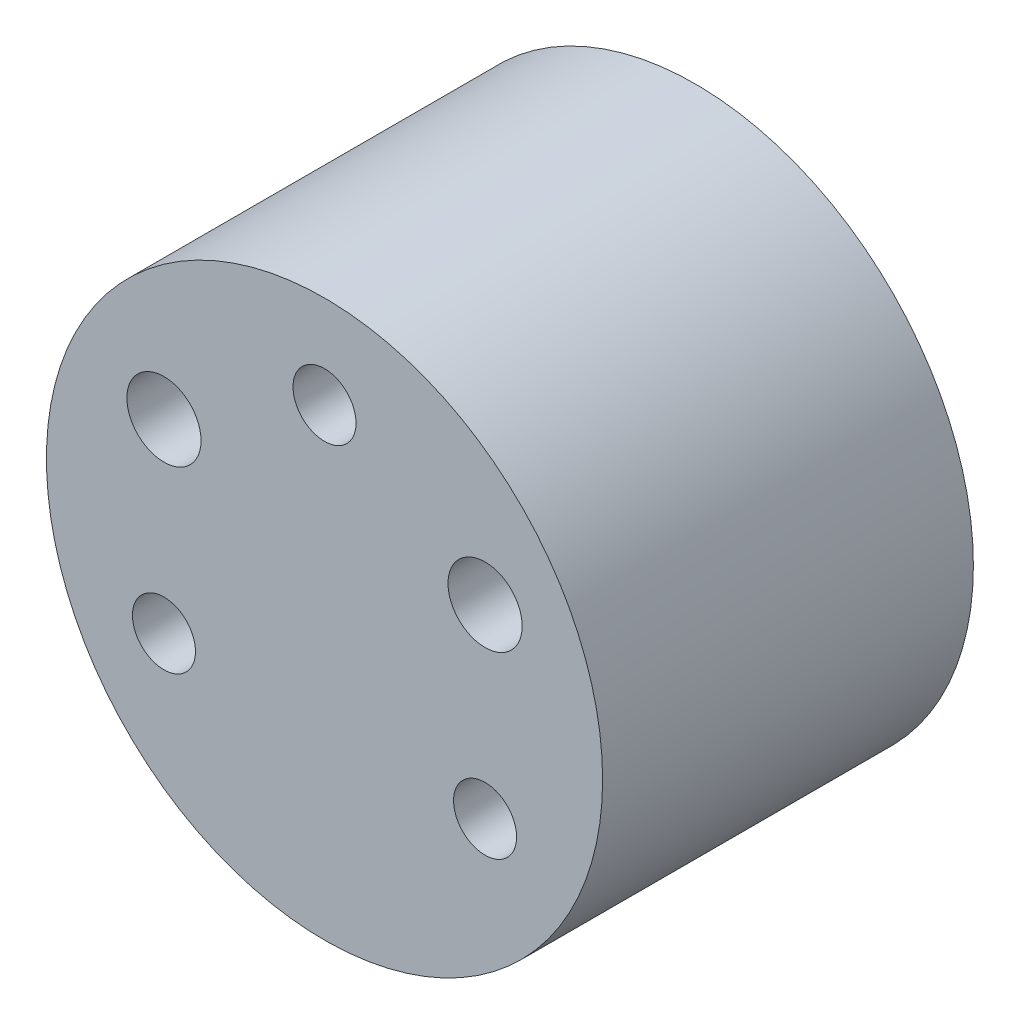
SolidWorks part; units mm, degrees
ref_plane "Plano frontal" through (0, 0, 0) normal (0, 0, 1) x (1, 0, 0)
ref_plane "Plano superior" through (0, 0, 0) normal (0, 1, 0) x (1, 0, 0)
ref_plane "Plano direito" through (0, 0, 0) normal (1, 0, 0) x (0, 0, -1)
sketch "Esboço1" plane through (0, 0, 0) normal (0, 0, 1) x (1, 0, 0)
  circle A0 centre (0, 235) radius 30 construction
  circle A1 centre (0, 235) radius 30
extrude "Ressalto-extrusão1" add sketch "Esboço1" along normal blind 40
hole_wizard "Furo roscado de M81" positions "Esboço2" profile "Esboço3" tap size "M8" standard "DIN"
sketch "Esboço2" plane through (0, 0, 40) normal (0, 0, 1) x (1, 0, 0)
  point P2 (-17.3205, 225)
  point P5 (0, 255)
  point P11 (17.3205, 225)
sketch "Esboço3" plane through (-17.3205, 225, 40) normal (1, 0, 0) x (0, -1, 0)
  line L0 (0, 0) -> (0, 32.0429)
  line L1 (0, 32.0429) -> (3.4, 30)
  line L2 (3.4, 30) -> (3.4, 0)
  line L5 (3.4, 0) -> (0, 0)
  line L10 (0, 32.0429) -> (-3.4, 30) construction
  line L11 (0, -6.35) -> (0, 107.95) construction
  dimension "Tap Drill Dia." = 6.8
  dimension "Tap Drill Depth" = 30
  dimension "Drill Angle" = 118
cosmetic thread "Rosca de furo1"
cosmetic thread "Rosca de furo2"
cosmetic thread "Rosca de furo3"
hole_wizard "Furos-guia com Ø8.0mm1" positions "Esboço4" profile "Esboço5" hole size "Ø8.0" standard "DIN"
sketch "Esboço4" plane through (0, 0, 40) normal (0, 0, 1) x (1, 0, 0)
  point P0 (17.3205, 245)
  point P3 (-17.3205, 245)
sketch "Esboço5" plane through (17.3205, 245, 40) normal (1, 0, 0) x (0, -1, 0)
  line L0 (0, 0) -> (0, 32.4034)
  line L1 (0, 32.4034) -> (4, 30)
  line L2 (4, 30) -> (4, 0)
  line L5 (4, 0) -> (0, 0)
  line L10 (0, 32.4034) -> (-4, 30) construction
  line L11 (0, -6.35) -> (0, 107.95) construction
  dimension "Hole Dia." = 8
  dimension "Hole Depth" = 30
  dimension "Drill Angle" = 118
